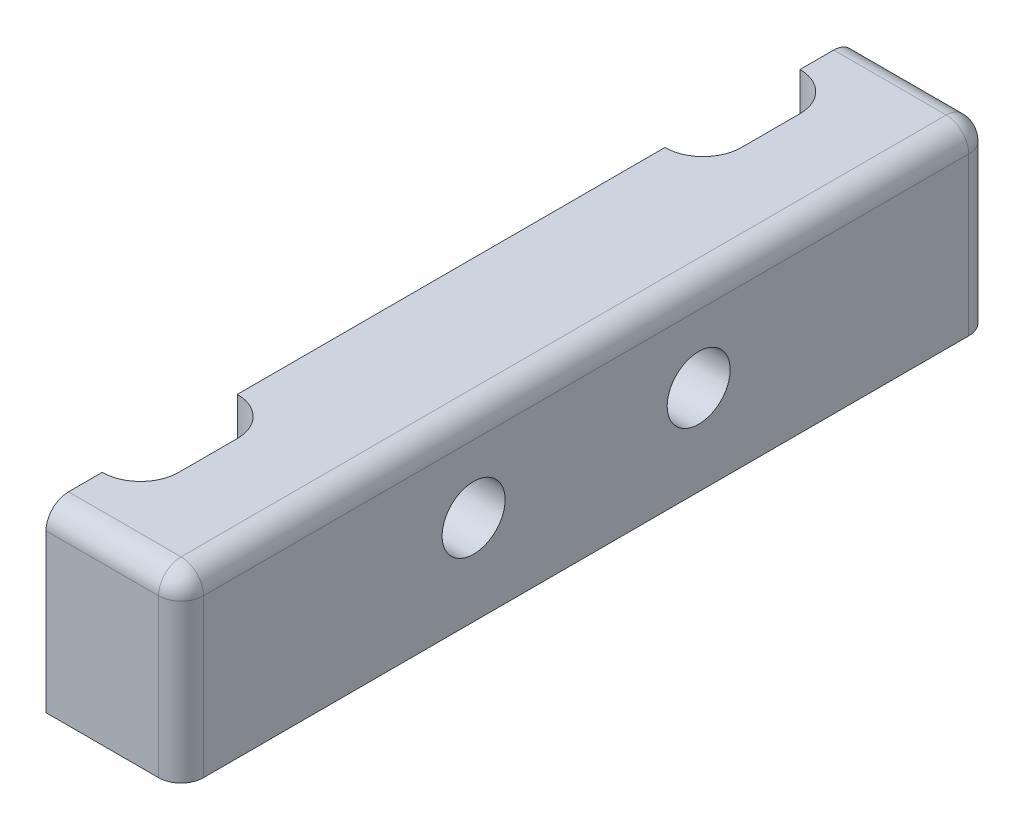
SolidWorks part; units mm, degrees
ref_plane "Front Plane" through (0, 0, 0) normal (0, 0, 1) x (1, 0, 0)
ref_plane "Top Plane" through (0, 0, 0) normal (0, 1, 0) x (1, 0, 0)
ref_plane "Right Plane" through (0, 0, 0) normal (1, 0, 0) x (0, 0, -1)
sketch "Sketch1" plane through (0, 0, 0) normal (0, 1, 0) x (1, 0, 0)
  line L0 (-6, 18) -> (-6, 15.5)
  line L1 (-6, 18) -> (0, 18)
  line L3 (-6, -18) -> (0, -18)
  line L4 (0, 18) -> (0, -18)
  line L5 (-6, 9.5) -> (-6, -9.5)
  line L6 (-6, -18) -> (-6, -15.5)
  line L7 (-4.3, -13.8) -> (-4.3, -11.2)
  line L8 (-4.3, 11.2) -> (-4.3, 13.8)
  arc A0 (-4.3, 13.8) -> (-6, 15.5) centre (-6, 13.8) ccw
  arc A1 (-4.3, 11.2) -> (-6, 9.5) centre (-6, 11.2) cw
  arc A2 (-4.3, -11.2) -> (-6, -9.5) centre (-6, -11.2) ccw
  arc A3 (-4.3, -13.8) -> (-6, -15.5) centre (-6, -13.8) cw
  point P4 (0, 0)
  point P20 (-4.3, 12.5)
  point P21 (-4.3, -12.5)
  dimension "D4" = 1.7
  dimension "D1" = 36
  dimension "D2" = 6
  dimension "D3" = 2.5
  dimension "D5" = 6
  dimension "D6" = 2.6
  dimension "D7" = 25
  dimension "D8" = 6
extrude "Base" add sketch "Sketch1" along normal blind 8
sketch "Sketch2" plane through (-6, 0, 0) normal (-1, 0, 0) x (0, 0, 1)
  line L0 (-9.5, 4) -> (9.5, 4) construction
  line L1 (-9.5, 8) -> (-9.5, 0) construction
  line L2 (9.5, 8) -> (9.5, 0) construction
  line L3 (0, 8) -> (0, 0) construction
  line L4 (-9.5, 8) -> (9.5, 8) construction
  circle A0 centre (-5, 4) radius 1.4
  circle A1 centre (5, 4) radius 1.4
  dimension "D1" = 4.5
  dimension "D2" = 2.8
extrude "Screw Holes" cut sketch "Sketch2" against normal through all
fillet "1mm Edge Fillets" radius 1 5 edges at (0, 4, -18) (-3, 8, -18) (0, 8, 0) (0, 4, 18) (-3, 8, 18)
